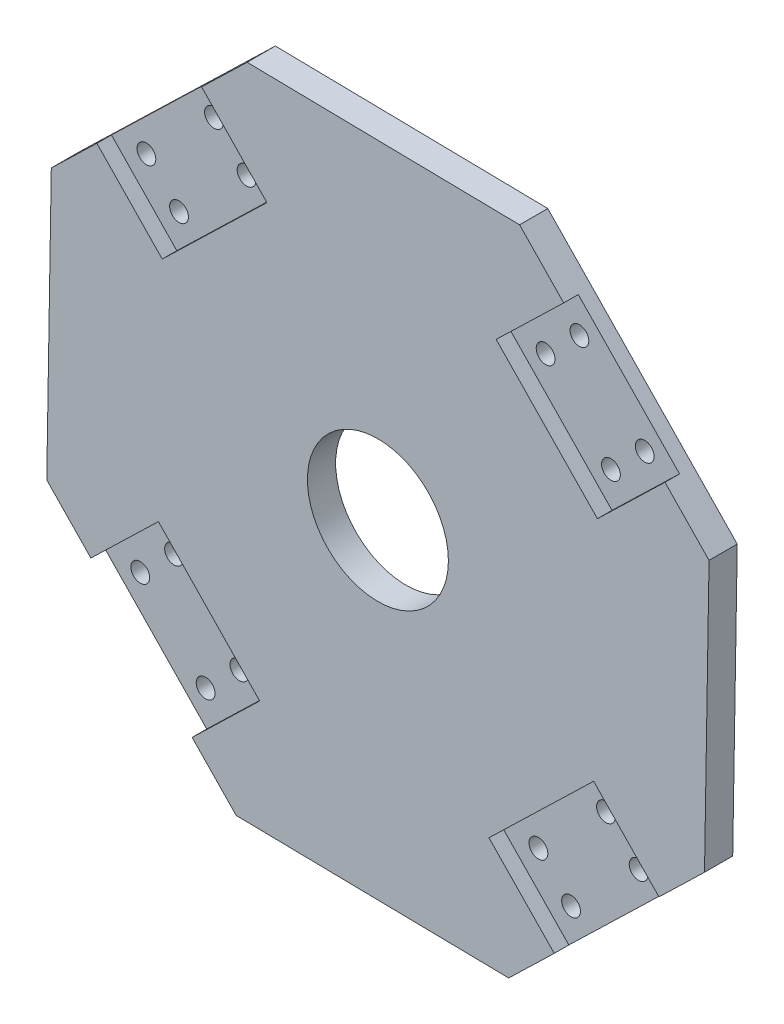
SolidWorks part; units mm, degrees
ref_plane "Plano frontal" through (0, 0, 0) normal (0, 0, 1) x (1, 0, 0)
ref_plane "Plano superior" through (0, 0, 0) normal (0, 1, 0) x (1, 0, 0)
ref_plane "Plano direito" through (0, 0, 0) normal (1, 0, 0) x (0, 0, -1)
sketch "Esboço2" plane through (0, 0, 0) normal (0, 0, 1) x (1, 0, 0)
  line L1 (70.4729, 27.8258) -> (30.1561, 69.5077)
  line L2 (30.1561, 69.5077) -> (-27.8258, 70.4729)
  line L3 (-27.8258, 70.4729) -> (-69.5077, 30.1561)
  line L4 (-69.5077, 30.1561) -> (-70.4729, -27.8258)
  line L5 (-70.4729, -27.8258) -> (-30.1561, -69.5077)
  line L6 (-30.1561, -69.5077) -> (27.8258, -70.4729)
  line L7 (27.8258, -70.4729) -> (69.5077, -30.1561)
  line L8 (69.5077, -30.1561) -> (70.4729, 27.8258)
  circle A0 centre (0, 0) radius 70 construction
  dimension "D1" = 140
  dimension "D2" = 140
extrude "Ressalto-extrusão1" add sketch "Esboço2" along normal blind 6 contours L3 L4 L5 L6 L7 L8 L1 L2
sketch "Esboço3" plane through (0, 0, 6) normal (0, 0, 1) x (1, 0, 0)
  line L0 (-61.0872, -37.5293) -> (-39.5348, -59.8114)
  line L1 (-70.4729, -27.8258) -> (-30.1561, -69.5077) construction
  line L2 (-39.5348, -59.8114) -> (-25.1592, -45.9066)
  line L3 (-25.1592, -45.9066) -> (-46.7116, -23.6245)
  line L4 (-46.7116, -23.6245) -> (-61.0872, -37.5293)
  line L5 (-48.6667, 50.3145) -> (48.6667, -50.3145) construction
  line L6 (-27.8258, 70.4729) -> (-69.5077, 30.1561) construction
  line L7 (27.8258, -70.4729) -> (69.5077, -30.1561) construction
  line L8 (46.7186, 23.6172) -> (25.1662, 45.8994)
  line L9 (61.0942, 37.522) -> (46.7186, 23.6172)
  line L10 (39.5418, 59.8042) -> (61.0942, 37.522)
  line L11 (25.1662, 45.8994) -> (39.5418, 59.8042)
  line L12 (-59.8042, 39.5418) -> (-37.522, 61.0942)
  line L13 (-37.522, 61.0942) -> (-23.6172, 46.7186)
  line L14 (-59.8042, 39.5418) -> (-45.8994, 25.1662)
  line L15 (-45.8994, 25.1662) -> (-23.6172, 46.7186)
  line L16 (-50.311, -48.6704) -> (50.318, 48.6631) construction
  line L17 (23.6315, -46.7189) -> (45.9137, -25.1665)
  line L18 (37.5363, -61.0945) -> (59.8184, -39.5421)
  line L19 (37.5363, -61.0945) -> (23.6315, -46.7189)
  line L20 (59.8184, -39.5421) -> (45.9137, -25.1665)
  dimension "D1" = 20
  dimension "D2" = 31
  dimension "D3" = 13.5
  dimension "D4" = 31
  dimension "D5" = 20
  dimension "D6" = 13.5
extrude "Corte-extrusão1" cut sketch "Esboço3" against normal blind 3.1
sketch "Esboço4" plane through (0, 0, 6) normal (0, 0, 1) x (1, 0, 0)
  circle A0 centre (0, 0) radius 15
  dimension "D1" = 30
extrude "Corte-extrusão2" cut sketch "Esboço4" against normal through all contours A0
sketch "Esboço6" plane through (0, 0, 2.9) normal (0, 0, 1) x (1, 0, 0)
  line L0 (-46.7116, -23.6245) -> (-61.0872, -37.5293) construction
  line L1 (-61.0872, -37.5293) -> (-39.5348, -59.8114) construction
  line L2 (-25.1592, -45.9066) -> (-46.7116, -23.6245) construction
  line L3 (23.6315, -46.7189) -> (37.5293, -61.0872) construction
  line L4 (59.8114, -39.5348) -> (37.5293, -61.0872) construction
  line L5 (45.9137, -25.1665) -> (23.6315, -46.7189) construction
  line L6 (59.8114, -39.5348) -> (45.9137, -25.1665) construction
  line L7 (0, 0) -> (50.318, 48.6631) construction
  line L8 (-39.5348, -59.8114) -> (-25.1592, -45.9066) construction
  line L9 (0, 0) -> (-48.6631, 50.318) construction
  line L10 (-37.522, 61.0942) -> (-59.8042, 39.5418) construction
  line L11 (61.0942, 37.522) -> (39.5418, 59.8042) construction
  circle A0 centre (-46.4817, -31.054) radius 2
  circle A1 centre (-53.6695, -38.0064) radius 2
  circle A4 centre (-39.7647, -52.3819) radius 2
  circle A5 centre (-32.5769, -45.4296) radius 2
  circle A6 centre (39.7793, 52.3689) radius 2
  circle A7 centre (32.5905, 45.4176) radius 2
  circle A8 centre (53.682, 37.9914) radius 2
  circle A9 centre (46.4932, 31.04) radius 2
  circle A10 centre (38.0064, -53.6695) radius 2
  circle A11 centre (31.061, -46.489) radius 2
  circle A12 centre (52.3819, -39.7647) radius 2
  circle A13 centre (45.4366, -32.5842) radius 2
  circle A14 centre (-37.9914, 53.682) radius 2
  circle A15 centre (-31.047, 46.5005) radius 2
  circle A16 centre (-45.4246, 32.5978) radius 2
  circle A17 centre (-52.3689, 39.7793) radius 2
  dimension "D2" = 4
  dimension "D3" = 4
  dimension "D4" = 5.5
  dimension "D9" = 5
  dimension "D8" = 4
  dimension "D11" = 5.5
  dimension "D7" = 4
  dimension "D12" = 5
  dimension "D13" = 4
  dimension "D14" = 4
  dimension "D15" = 4
  dimension "D16" = 4
  dimension "D17" = 5.5
  dimension "D19" = 5.5
  dimension "D20" = 5
  dimension "D21" = 5
  dimension "D22" = 5.5
  dimension "D24" = 5
  dimension "D1" = 5.5
  dimension "D5" = 5
  dimension "D6" = 5
  dimension "D10" = 5.5
  dimension "D18" = 5
  dimension "D23" = 5.5
extrude "Corte-extrusão3" cut sketch "Esboço6" against normal blind 3.1
